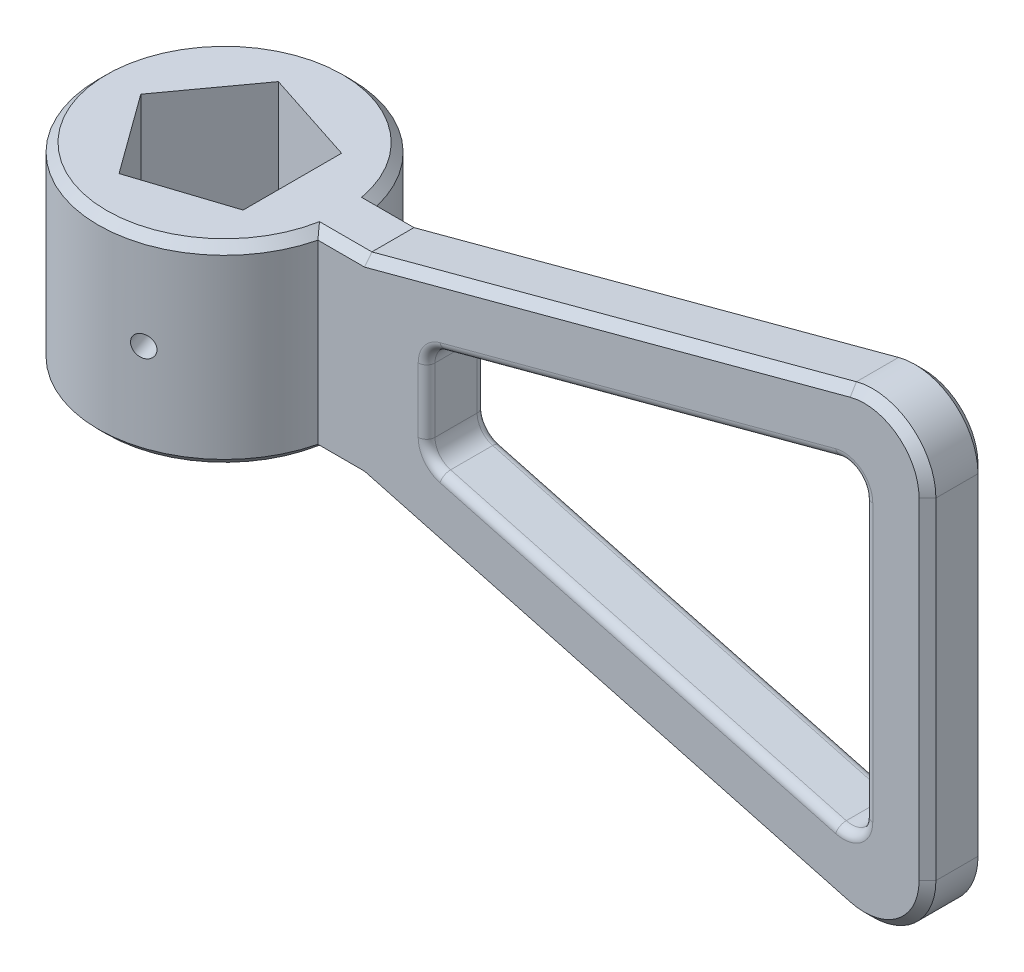
SolidWorks part; units mm, degrees
ref_plane "Front Plane" through (0, 0, 0) normal (0, 0, 1) x (1, 0, 0)
ref_plane "Top Plane" through (0, 0, 0) normal (0, 1, 0) x (1, 0, 0)
ref_plane "Right Plane" through (0, 0, 0) normal (1, 0, 0) x (0, 0, -1)
sketch "Sketch1" plane through (0, 0, 0) normal (0, 0, 1) x (1, 0, 0)
  line L0 (0, 0) -> (210.8013, 0) construction
  line L1 (0, 0) -> (0, 83.6342) construction
  line L31 (174, -39.3568) -> (174, 39.3568)
  line L32 (155.1177, 53.8457) -> (40, 23)
  line L35 (155.1177, -53.8457) -> (40, -23)
  line L38 (159, -39.3568) -> (159, 39.3568)
  line L39 (159, 39.3568) -> (55, 11.4901)
  line L40 (55, 11.4901) -> (55, -11.4901)
  line L41 (159, -39.3568) -> (55, -11.4901)
  line L42 (40, 23) -> (30, 23)
  line L44 (30, -23) -> (40, -23)
  line L45 (30, 23) -> (0, 23)
  line L46 (40, 23) -> (40, -23) construction
  line L47 (0, 23) -> (0, -23)
  line L48 (0, -23) -> (30, -23)
  arc A9 (174, 39.3568) -> (155.1177, 53.8457) centre (159, 39.3568) ccw
  arc A10 (174, -39.3568) -> (155.1177, -53.8457) centre (159, -39.3568) cw
  arc A11 (159, 39.3568) -> (159, 39.3568) centre (159, 39.3568) ccw
  arc A12 (159, -39.3568) -> (159, -39.3568) centre (159, -39.3568) cw
  point P11 (174, 0)
  dimension "D1" = 46
  dimension "D7" = 10
  dimension "D2" = 15
  dimension "D4" = 30
  dimension "D5" = 174
  dimension "D6" = 15
extrude "Boss-Extrude2" add sketch "Sketch1" along normal mid plane 14
sketch "Sketch2" plane through (0, 0, 0) normal (0, 1, 0) x (1, 0, 0)
  circle A0 centre (0, 0) radius 30
  dimension "D1" = 60
extrude "Boss-Extrude4" add sketch "Sketch2" along normal mid plane 46
sketch "Sketch3" plane through (0, 23, 0) normal (0, 1, 0) x (1, 0, 0)
  line L1 (16.0997, 11.6971) -> (-6.1495, 18.9263)
  line L2 (-6.1495, 18.9263) -> (-19.9003, 0)
  line L3 (-19.9003, 0) -> (-6.1495, -18.9263)
  line L4 (-6.1495, -18.9263) -> (16.0997, -11.6971)
  line L5 (16.0997, -11.6971) -> (16.0997, 11.6971)
  circle A0 centre (0, 0) radius 16.0997 construction
  point P1 (15.5297, 10.9243)
  point P7 (-6.3288, 18.9838)
  dimension "D1" = 36
extrude "Cut-Extrude1" cut sketch "Sketch3" against normal blind 46
sketch "Sketch4" plane through (4.9751, 0, 15.3117) normal (-0.309, 0, -0.9511) x (-0.9511, 0, 0.309)
  circle A0 centre (0, 0) radius 2.5
  dimension "D1" = 5
extrude "Cut-Extrude2" cut sketch "Sketch4" against normal up to next
fillet "Fillet1" radius 5 4 edges at (159, -39.3568, 0) (159, 39.3568, 0) (55, -11.4901, 0) (55, 11.4901, 0)
chamfer "Chamfer1" distance 2 angle 45 16 edges at (34.586, -23, -7) (-30, 23, 0) (-30, -23, 0) (34.586, -23, 7) (97.5589, -38.4228, 7) (97.5589, -38.4228, -7) (168.1314, -51.2571, 7) (168.1314, -51.2571, -7) (174, 0, 7) (174, 0, -7) (168.1314, 51.2571, 7) (168.1314, 51.2571, -7) (97.5589, 38.4228, -7) (34.586, 23, -7) (34.586, 23, 7) (97.5589, 38.4228, 7)
fillet "Fillet2" radius 2 16 edges at (56.0332, -10.6973, -7) (55, 0, -7) (56.0332, 10.6973, -7) (105.7059, 25.0767, -7) (157.0438, 36.8075, -7) (159, 0, -7) (157.0438, -36.8075, -7) (56.0332, -10.6973, 7) (55, 0, 7) (56.0332, 10.6973, 7) (105.7059, 25.0767, 7) (157.0438, 36.8075, 7) (159, 0, 7) (157.0438, -36.8075, 7) (105.7059, -25.0767, -7) (105.7059, -25.0767, 7)
